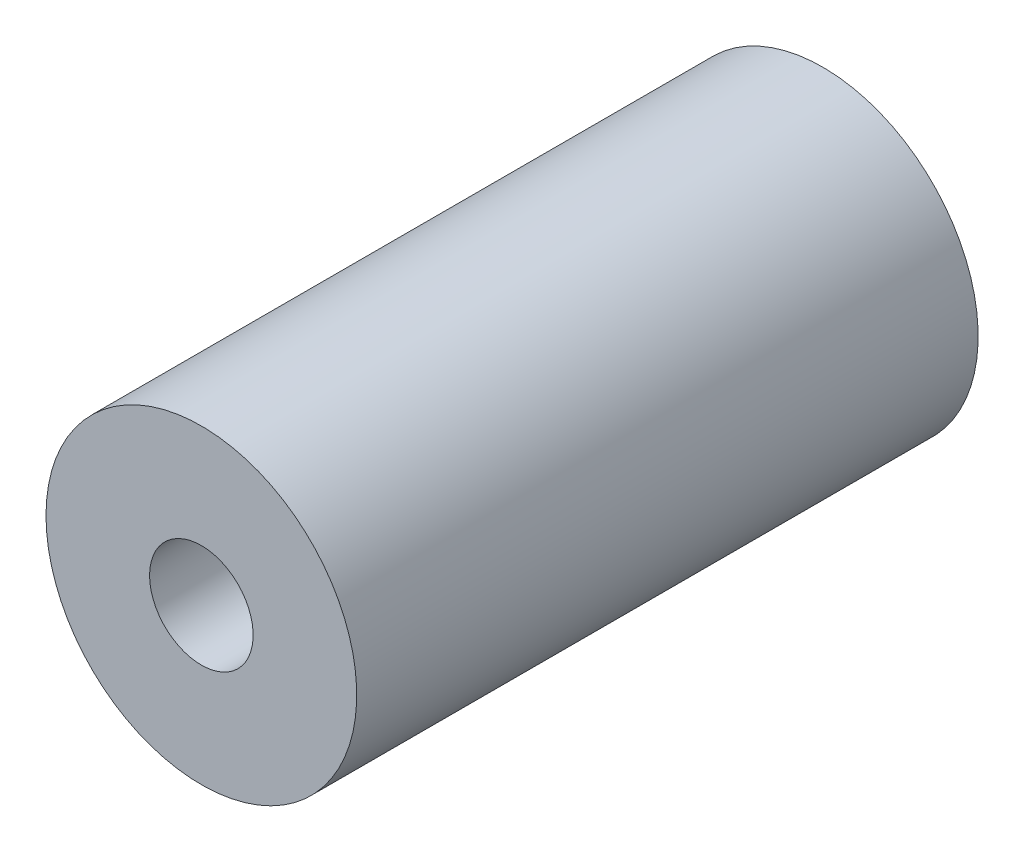
SolidWorks part; units mm, degrees
material "Silicon Rubber"
ref_plane "Front" through (0, 0, 0) normal (0, 0, 1) x (1, 0, 0)
ref_plane "Top" through (0, 0, 0) normal (0, 1, 0) x (1, 0, 0)
ref_plane "Right" through (0, 0, 0) normal (1, 0, 0) x (0, 0, -1)
sketch "Sketch1" plane through (0, 0, 0) normal (0, 0, 1) x (1, 0, 0)
  circle A0 centre (0, 0) radius 3.175
  circle A1 centre (0, 0) radius 9.525
  dimension "D1" = 6.35
  dimension "D2" = 19.05
extrude "Boss-Extrude1" add sketch "Sketch1" along normal blind 38.1
